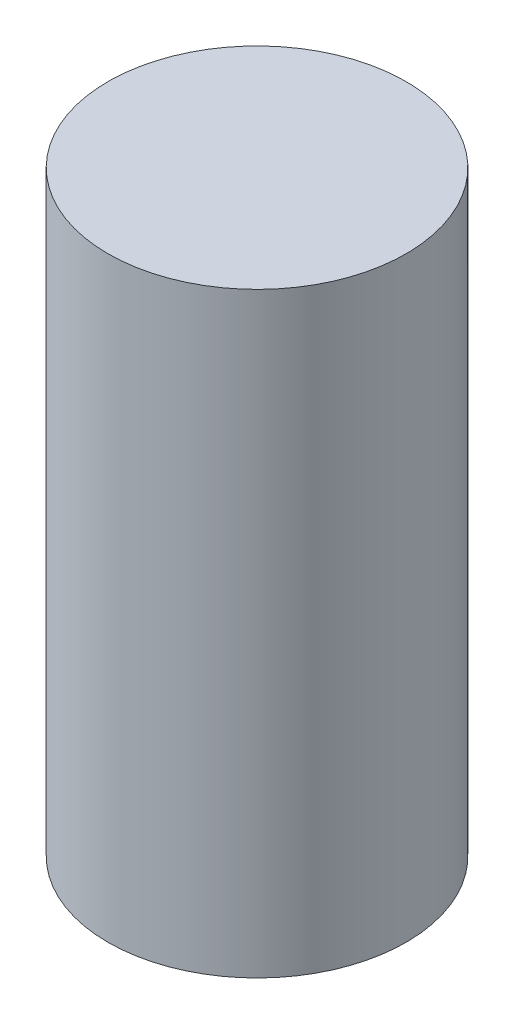
SolidWorks part; units mm, degrees
material "1060 Alloy"
ref_plane "Front Plane" through (0, 0, 0) normal (0, 0, 1) x (1, 0, 0)
ref_plane "Top Plane" through (0, 0, 0) normal (0, 1, 0) x (1, 0, 0)
ref_plane "Right Plane" through (0, 0, 0) normal (1, 0, 0) x (0, 0, -1)
sketch "Sketch1" plane through (0, 0, 0) normal (0, 1, 0) x (1, 0, 0)
  circle A0 centre (0, 0) radius 12.5
  dimension "D1" = 25
extrude "Boss-Extrude1" add sketch "Sketch1" along normal mid plane 50
